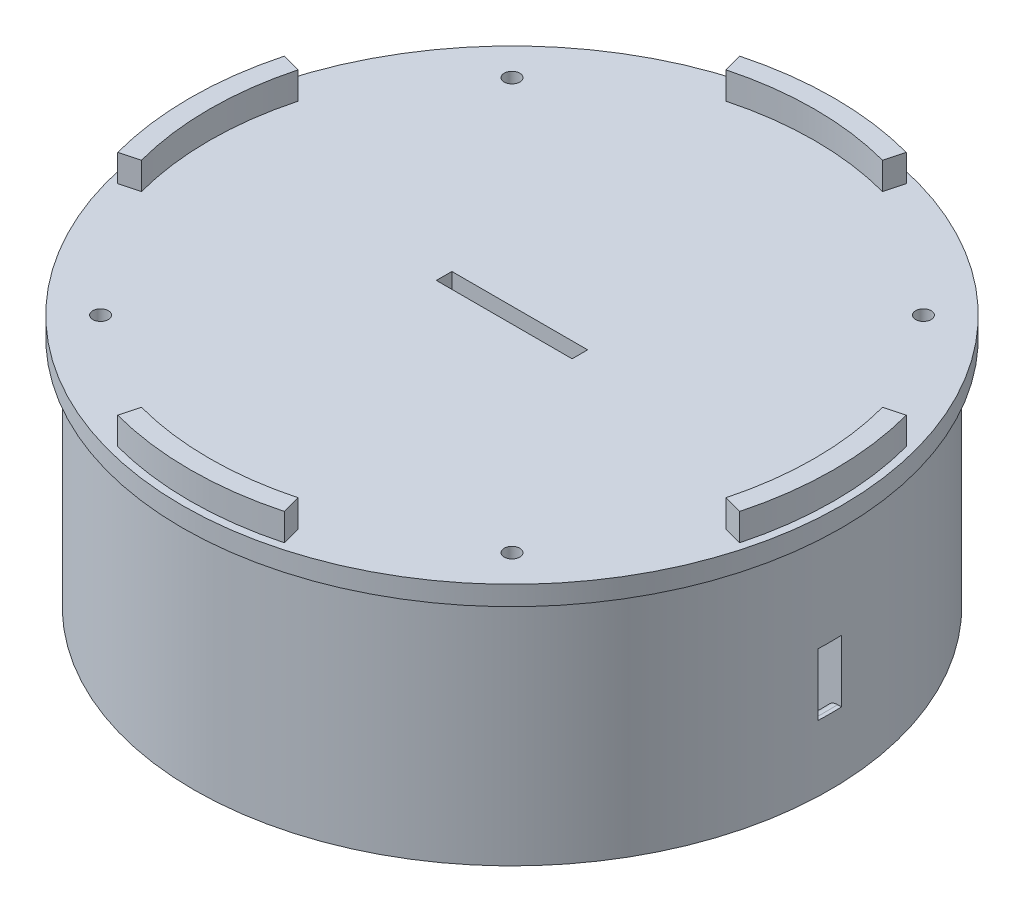
SolidWorks part; units mm, degrees
ref_plane "Front Plane" through (0, 0, 0) normal (0, 0, 1) x (1, 0, 0)
ref_plane "Top Plane" through (0, 0, 0) normal (0, 1, 0) x (1, 0, 0)
ref_plane "Right Plane" through (0, 0, 0) normal (1, 0, 0) x (0, 0, -1)
sketch "Sketch1" plane through (0, 0, 0) normal (0, 1, 0) x (1, 0, 0)
  line L0 (-85, 0) -> (85, 0) construction
  line L1 (0, 85) -> (0, -85) construction
  circle A0 centre (0, 0) radius 85
  dimension "D1" = 170
extrude "Boss-Extrude1" add sketch "Sketch1" along normal blind 5
sketch "Sketch14" plane through (0, 5, 0) normal (0, 1, 0) x (1, 0, 0)
  circle A0 centre (-53.033, 53.033) radius 2
  circle A1 centre (53.033, 53.033) radius 2
  circle A2 centre (53.033, -53.033) radius 2
  circle A3 centre (-53.033, -53.033) radius 2
  point P14 (0, 0)
  dimension "D1" = 75
  dimension "D2" = 4
extrude "Cut-Extrude2" cut sketch "Sketch14" against normal blind 133
sketch "Sketch15" plane through (0, 5, 0) normal (0, 1, 0) x (1, 0, 0)
  line L0 (0, 85) -> (0, -85) construction
  line L1 (-49.533, 55.0537) -> (-53.033, 57.0745)
  line L2 (-53.033, 57.0745) -> (-56.533, 55.0537)
  line L3 (-56.533, 55.0537) -> (-56.533, 51.0123)
  line L4 (-56.533, 51.0123) -> (-53.033, 48.9916)
  line L5 (-53.033, 48.9916) -> (-49.533, 51.0123)
  line L6 (-49.533, 51.0123) -> (-49.533, 55.0537)
  line L7 (55.0537, 49.533) -> (57.0745, 53.033)
  line L8 (57.0745, 53.033) -> (55.0537, 56.533)
  line L9 (55.0537, 56.533) -> (51.0123, 56.533)
  line L10 (51.0123, 56.533) -> (48.9916, 53.033)
  line L11 (48.9916, 53.033) -> (51.0123, 49.533)
  line L12 (51.0123, 49.533) -> (55.0537, 49.533)
  line L13 (49.533, -55.0537) -> (53.033, -57.0745)
  line L14 (53.033, -57.0745) -> (56.533, -55.0537)
  line L15 (56.533, -55.0537) -> (56.533, -51.0123)
  line L16 (56.533, -51.0123) -> (53.033, -48.9916)
  line L17 (53.033, -48.9916) -> (49.533, -51.0123)
  line L18 (49.533, -51.0123) -> (49.533, -55.0537)
  line L19 (-55.0537, -49.533) -> (-57.0745, -53.033)
  line L20 (-57.0745, -53.033) -> (-55.0537, -56.533)
  line L21 (-55.0537, -56.533) -> (-51.0123, -56.533)
  line L22 (-51.0123, -56.533) -> (-48.9916, -53.033)
  line L23 (-48.9916, -53.033) -> (-51.0123, -49.533)
  line L24 (-51.0123, -49.533) -> (-55.0537, -49.533)
  circle A0 centre (-53.033, 53.033) radius 3.5 construction
  point P32 (0, 0)
  dimension "D1" = 7
  dimension "D2" = 4
sketch "Sketch16" plane through (0, 5, 0) normal (0, 1, 0) x (1, 0, 0)
  line L1 (-17.5, 2) -> (17.5, 2)
  line L2 (-17.5, 2) -> (-17.5, -2)
  line L3 (-17.5, -2) -> (17.5, -2)
  line L4 (17.5, 2) -> (17.5, -2)
  line L5 (-17.5, 2) -> (17.5, -2) construction
  line L6 (-17.5, -2) -> (17.5, 2) construction
  point P0 (0, 0)
  dimension "D1" = 4
  dimension "D2" = 35
extrude "Cut-Extrude4" cut sketch "Sketch16" against normal blind 10
sketch "Sketch19" plane through (0, 5, 0) normal (0, 1, 0) x (1, 0, 0)
  line L0 (75.3422, 20.1879) -> (80.1718, 21.482)
  line L1 (75.3422, -20.1879) -> (80.1718, -21.482)
  line L2 (20.1879, -75.3422) -> (21.482, -80.1718)
  line L3 (-20.1879, -75.3422) -> (-21.482, -80.1718)
  line L4 (-75.3422, -20.1879) -> (-80.1718, -21.482)
  line L5 (-75.3422, 20.1879) -> (-80.1718, 21.482)
  line L6 (-20.1879, 75.3422) -> (-21.482, 80.1718)
  line L7 (20.1879, 75.3422) -> (21.482, 80.1718)
  arc A2 (80.1718, -21.482) -> (80.1718, 21.482) centre (0, 0) ccw
  arc A3 (75.3422, -20.1879) -> (75.3422, 20.1879) centre (0, 0) ccw
  arc A4 (-20.1879, -75.3422) -> (20.1879, -75.3422) centre (0, 0) ccw
  arc A5 (-21.482, -80.1718) -> (21.482, -80.1718) centre (0, 0) ccw
  arc A6 (-75.3422, 20.1879) -> (-75.3422, -20.1879) centre (0, 0) ccw
  arc A7 (-80.1718, 21.482) -> (-80.1718, -21.482) centre (0, 0) ccw
  arc A8 (20.1879, 75.3422) -> (-20.1879, 75.3422) centre (0, 0) ccw
  arc A9 (21.482, 80.1718) -> (-21.482, 80.1718) centre (0, 0) ccw
  point P19 (0, 0)
extrude "Boss-Extrude2" add sketch "Sketch19" along normal blind 7
sketch "Sketch20" plane through (0, 0, 0) normal (0, -1, 0) x (1, 0, 0)
  circle A0 centre (0, 0) radius 82
  circle A1 centre (0, 0) radius 78
extrude "Boss-Extrude3" add sketch "Sketch20" along normal blind 60
sketch "Sketch22" plane through (0, 0, 0) normal (0, -1, 0) x (1, 0, 0)
  line L0 (-65, -3) -> (-65, -7)
  line L1 (-80.697, 7) -> (-65, 7)
  line L2 (-85, -3) -> (85, -3)
  line L3 (-80.9444, -3) -> (-65, -3)
  line L4 (-85, 3) -> (85, 3)
  line L5 (-80.9444, 3) -> (-65, 3)
  line L6 (-80.697, -7) -> (-65, -7)
  line L7 (-65, 7) -> (-65, 3)
  line L8 (0, 39.3916) -> (0, -39.311) construction
  line L9 (-85, 7) -> (85, 7) construction
  line L10 (0, -85) -> (0, 85) construction
  line L11 (-85, 3) -> (85, 3) construction
  line L12 (65, 7) -> (65, 3)
  line L13 (-85, -3) -> (85, -3) construction
  line L14 (80.697, -7) -> (65, -7)
  line L15 (-85, -7) -> (85, -7) construction
  line L16 (80.9444, 3) -> (65, 3)
  line L17 (80.9444, -3) -> (65, -3)
  line L18 (80.697, 7) -> (65, 7)
  line L19 (65, -3) -> (65, -7)
  arc A0 (-80.9444, -3) -> (-80.697, -7) centre (0, 0) ccw
  arc A1 (80.697, 7) -> (80.9444, 3) centre (0, 0) cw
  circle A2 centre (0, 0) radius 81
  arc A3 (-80.697, 7) -> (-80.9444, 3) centre (0, 0) ccw
  arc A4 (80.9444, -3) -> (80.697, -7) centre (0, 0) cw
  circle M13 centre (0, 0) radius 78
  dimension "D2" = 65
  dimension "D1" = 3
  dimension "D3" = 3
  dimension "D4" = 3
  dimension "D5" = 4
  dimension "D6" = 4
extrude "Boss-Extrude4" add sketch "Sketch22" along normal blind 60 contours L6 L0 L3 M13 | L3 A0 L6 M13 | A1 L18 L16 M13 | L18 L12 L16 M13 | L17 L19 L14 M13 | A4 L17 L14 M13 | L1 L7 L5 A3
sketch "Sketch23" plane through (0, 0, 7) normal (0, 0, 1) x (1, 0, 0)
  line L0 (85, 0) -> (-85, 0) construction
  line L1 (-82, 0) -> (-82, -60) construction
  circle A0 centre (-70, -30) radius 1.5
  dimension "D1" = 3
  dimension "D2" = 30
  dimension "D3" = 12
extrude "Cut-Extrude5" cut sketch "Sketch23" against normal blind 25
mirror "Mirror1" about plane through (0, 0, 0) normal (1, 0, 0) of "Cut-Extrude5"
sketch "Sketch25" plane through (0, 0, 0) normal (1, 0, 0) x (0, 0, -1)
  line L0 (85, 0) -> (-85, 0) construction
  line L1 (-3, -27) -> (3, -27)
  line L2 (-3, -27) -> (-3, -33)
  line L4 (3, -27) -> (3, -33)
  line L5 (-3, -27) -> (3, -33) construction
  line L6 (-3, -33) -> (3, -27) construction
  line L9 (-3, -33) -> (-3, -43)
  line L10 (-3, -43) -> (3, -43)
  line L11 (3, -33) -> (3, -43)
  point P0 (0, -30)
  dimension "D1" = 30
  dimension "D2" = 6
  dimension "D3" = 6
  dimension "D4" = 10
extrude "Cut-Extrude6" cut sketch "Sketch25" against normal blind 105 and the other way blind 110
fillet "Fillet1" radius 3 4 edges at (-78, -27, 0) (78, -27, 0) (-78, -43, 0) (78, -43, 0)
sketch "Sketch27" plane through (0, -60, 0) normal (0, -1, 0) x (1, 0, 0)
  line L0 (-77.6853, -7) -> (-65, -7) construction
  line L1 (-65, 7) -> (-79, 7)
  line L2 (-65, 7) -> (-65, -7)
  line L3 (-65, -7) -> (-79, -7)
  line L4 (-79, 7) -> (-79, -7)
  dimension "D1" = 14
extrude "Boss-Extrude5" add sketch "Sketch27" against normal blind 5
mirror "Mirror2" about plane through (0, 0, 0) normal (1, 0, 0) of "Boss-Extrude5"
pattern_circular "CirPattern1" count 2 every 90 about axis through (0, 0, 0) along (0, 1, 0) of "Boss-Extrude4", "Boss-Extrude5", "Mirror2"
sketch "Sketch29" plane through (0, -60, 0) normal (0, -1, 0) x (1, 0, 0)
  line L0 (-85, 0) -> (85, 0) construction
  circle A0 centre (-72.5, 0) radius 1.25
  point P4 (0, 0)
  dimension "D1" = 2.5
  dimension "D2" = 72.5
extrude "Cut-Extrude7" cut sketch "Sketch29" against normal blind 5
pattern_circular "CirPattern2" count 4 every 90 about axis through (0, 0, 0) along (0, 1, 0) of "Cut-Extrude7"
